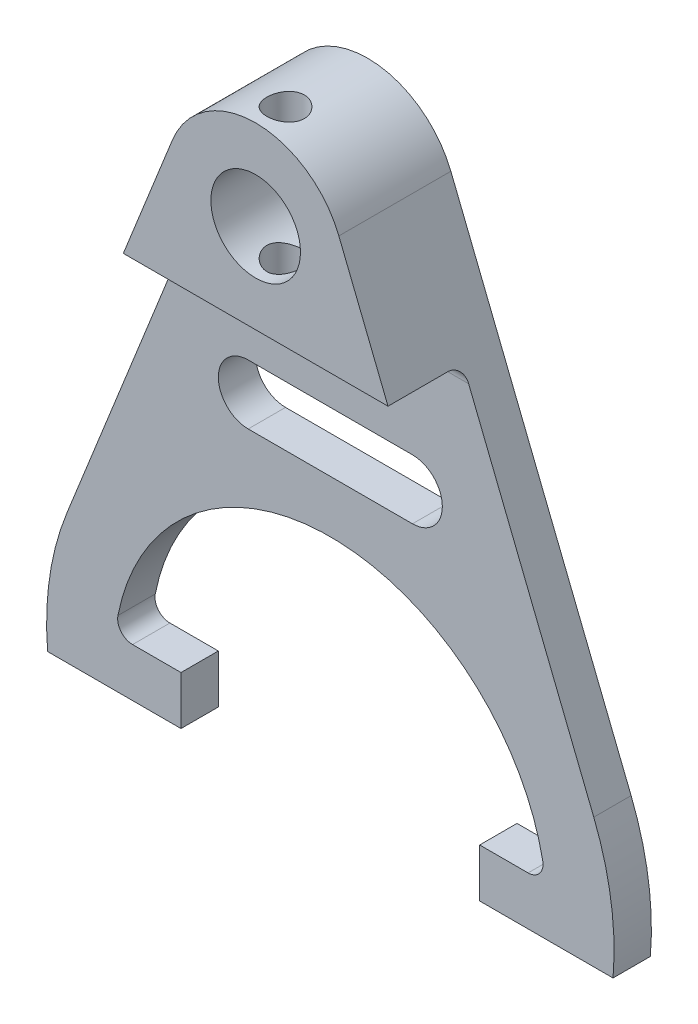
SolidWorks part; units mm, degrees
ref_plane "Piano frontale" through (0, 0, 0) normal (0, 0, 1) x (1, 0, 0)
ref_plane "Piano superiore" through (0, 0, 0) normal (0, 1, 0) x (1, 0, 0)
ref_plane "Piano destro" through (0, 0, 0) normal (1, 0, 0) x (0, 0, -1)
sketch "Schizzo2" plane through (0, 0, 0) normal (0, 0, 1) x (1, 0, 0)
  line L0 (-11.1415, 4.4571) -> (-35.2815, -55.8857)
  line L1 (11.1415, 4.4571) -> (35.2815, -55.8857)
  line L2 (0, 0) -> (0, -76.8675) construction
  line L3 (-57.0654, -70) -> (61.9409, -70) construction
  line L4 (28.8173, -66.75) -> (20, -66.75)
  line L5 (20, -66.75) -> (20, -73.25)
  line L6 (38, -73.25) -> (20, -73.25)
  line L7 (38, -73.25) -> (38, -70)
  line L8 (-38, -73.25) -> (-38, -70)
  line L9 (-38, -73.25) -> (-20, -73.25)
  line L10 (-20, -66.75) -> (-20, -73.25)
  line L11 (-28.8173, -66.75) -> (-20, -66.75)
  arc A0 (11.1415, 4.4571) -> (-11.1415, 4.4571) centre (0, 0) ccw
  arc A2 (-35.2815, -55.8857) -> (-37.8608, -73.25) centre (0, -70) ccw
  arc A3 (37.8608, -73.25) -> (35.2815, -55.8857) centre (0, -70) ccw
  arc A4 (28.8173, -66.75) -> (-28.8173, -66.75) centre (0, -70) ccw
  point P16 (20, -70)
  point P24 (0, 0)
  point P25 (0, 0)
  point P26 (0, 0)
  point P27 (-18.7366, 4.7588)
  point P28 (17.3637, 4.7588)
  point P29 (0, 0)
  point P30 (0, 0)
  dimension "D1" = 24
  dimension "D2" = 29
  dimension "D8" = 76
  dimension "D3" = 70
  dimension "D4" = 40
  dimension "D5" = 6.5
  dimension "D7" = 76
extrude "Estrusione-Estrusione1" add sketch "Schizzo2" along normal blind 5 contours A4 L4 L5 L6 A3 L1 A0 L0 A2 L9 L10 L11
sketch "Schizzo3" plane through (0, 0, 5) normal (0, 0, 1) x (1, 0, 0)
  line L0 (-17.7252, -12) -> (17.7252, -12)
  line L1 (-11.1415, 4.4571) -> (-35.2815, -55.8857) construction
  line L2 (11.1415, 4.4571) -> (35.2815, -55.8857) construction
  line L3 (-17.7252, -12) -> (-11.1415, 4.4571)
  line L4 (17.7252, -12) -> (11.1415, 4.4571)
  arc A0 (11.1415, 4.4571) -> (-11.1415, 4.4571) centre (0, 0) ccw
  dimension "D1" = 12
extrude "Estrusione-Estrusione2" add sketch "Schizzo3" along normal blind 10
fillet "Raccordo1" radius 2 3 edges at (0, -12, 5) (28.8173, -66.75, 2.5) (-28.8173, -66.75, 2.5)
hole_wizard "Foro Ø12.0 (12)-1" positions "Schizzo4" profile "Schizzo5" hole size "Ø12.0" standard "ISO" end condition up to next
sketch "Schizzo4" plane through (0, 0, 15) normal (0, 0, 1) x (1, 0, 0)
  point P0 (0, 0)
sketch "Schizzo5" plane through (0, 0, 15) normal (1, 0, 0) x (0, -1, 0)
  line L0 (0, 0) -> (0, 15)
  line L1 (0, 15) -> (6, 15)
  line L2 (6, 15) -> (6, 0)
  line L5 (6, 0) -> (0, 0)
  line L11 (0, -6.35) -> (0, 107.95) construction
  dimension "Thru Hole Dia." = 12
  dimension "Thru Hole Depth" = 15
hole_wizard "Foro Ø5.0 (5)-2" positions "Schizzo9" profile "Schizzo10" hole size "Ø5.0" standard "ISO" end condition through all
sketch "Schizzo9" plane through (0, -12, 0) normal (0, -1, 0) x (-1, 0, 0)
  line L0 (-17.7252, -11) -> (17.7252, -11) construction
  line L1 (-17.7252, -15) -> (-17.7252, -7) construction
  line L2 (17.7252, -15) -> (17.7252, -7) construction
  line L3 (0, 6.3) -> (0, -21.8733) construction
  point P13 (0, -11)
sketch "Schizzo10" plane through (0, -12, 11) normal (1, 0, 0) x (0, 0, -1)
  line L0 (0, 0) -> (0, 24)
  line L1 (0, 24) -> (2.5, 24)
  line L2 (2.5, 24) -> (2.5, 0)
  line L5 (2.5, 0) -> (0, 0)
  line L11 (0, -6.35) -> (0, 107.95) construction
  dimension "Thru Hole Dia." = 5
  dimension "Thru Hole Depth" = 24
sketch "Schizzo8" plane through (0, 0, 5) normal (0, 0, 1) x (1, 0, 0)
  line L0 (-11, -30) -> (11, -30) construction
  line L1 (-11, -26) -> (11, -26)
  line L2 (-11, -34) -> (11, -34)
  line L3 (0, 2.8417) -> (0, -60.8817) construction
  arc A0 (-11, -26) -> (-11, -34) centre (-11, -30) ccw
  arc A1 (11, -34) -> (11, -26) centre (11, -30) ccw
  point P2 (0, -30)
  point P10 (0, 0)
  dimension "D3" = 4
  dimension "D1" = 30
  dimension "D2" = 22
extrude "Taglio-Estrusione1" cut sketch "Schizzo8" against normal up to next
sketch "Schizzo11" plane through (0, 0, 0) normal (0, 0, -1) x (-1, 0, 0)
  line L0 (0, 0) -> (0, -75.6237)
